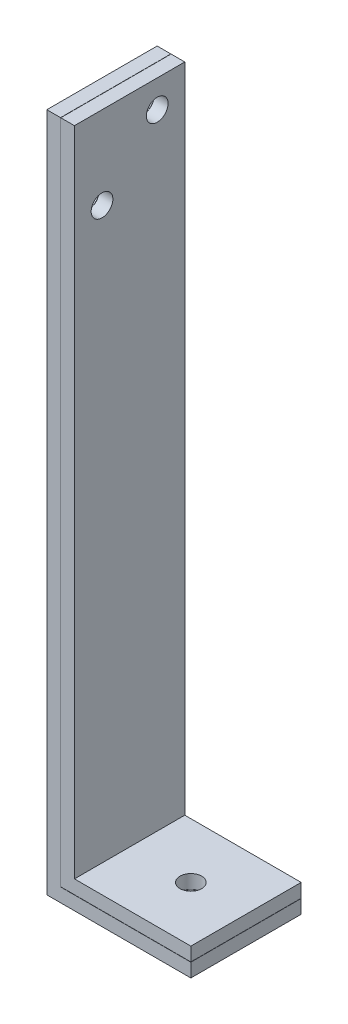
SolidWorks part; units mm, degrees
ref_plane "Alzado" through (0, 0, 0) normal (0, 0, 1) x (1, 0, 0)
ref_plane "Planta" through (0, 0, 0) normal (0, 1, 0) x (1, 0, 0)
ref_plane "Vista lateral" through (0, 0, 0) normal (1, 0, 0) x (0, 0, -1)
sketch "Croquis1" plane through (0, 0, 0) normal (0, 0, 1) x (1, 0, 0)
  line L0 (0, 0) -> (66.31, 0)
  line L1 (0, 0) -> (0, 313.04)
  line L2 (6.31, 6.31) -> (66.31, 6.31)
  line L3 (6.31, 6.31) -> (6.31, 313.04)
  line L4 (66.31, 6.31) -> (66.31, 0)
  line L5 (6.31, 313.04) -> (0, 313.04)
  dimension "D1" = 66.31
  dimension "D2" = 313.04
  dimension "D3" = 6.31
extrude "Saliente-Extruir1" add sketch "Croquis1" along normal blind 50.8
sketch "Croquis2" plane through (0, 0, 50.8) normal (0, 0, 1) x (1, 0, 0)
  line L0 (6.41, 313.04) -> (12.72, 313.04)
  line L1 (12.72, 313.04) -> (12.72, 12.72)
  line L2 (12.72, 12.72) -> (66.31, 12.72)
  line L3 (66.31, 12.72) -> (66.31, 6.41)
  line L4 (66.31, 6.41) -> (6.41, 6.41)
  line L5 (6.41, 6.41) -> (6.41, 313.04)
  line L6 (6.31, 6.31) -> (6.31, 313.04) construction
  line L7 (66.31, 6.31) -> (6.31, 6.31) construction
  line L9 (66.31, 6.31) -> (66.31, 6.9586) construction
  line L10 (6.31, 313.04) -> (0, 313.04) construction
  line L11 (3.155, 313.04) -> (16.3816, 313.04) construction
  dimension "D1" = 0.1
  dimension "D2" = 0.1
  dimension "D3" = 6.31
  dimension "D4" = 6.31
extrude "Saliente-Extruir2" add sketch "Croquis2" against normal blind 50.8 separate body
sketch "Croquis3" plane through (0, 0, 0) normal (-1, 0, 0) x (0, 0, 1)
  line L0 (0, 313.04) -> (50.8, 313.04) construction
  line L1 (50.8, 313.04) -> (50.8, 262.24) construction
  line L2 (50.8, 313.04) -> (50.8, 0) construction
  line L3 (50.8, 262.24) -> (0, 262.24) construction
  line L4 (0, 313.04) -> (0, 0) construction
  line L5 (0, 262.24) -> (0, 313.04) construction
  line L6 (0, 262.24) -> (50.8, 313.04) construction
  line L7 (50.8, 313.04) -> (25.4, 287.64) construction
  line L8 (25.4, 287.64) -> (38.1, 300.34) construction
  line L9 (50.8, 262.24) -> (0, 313.04) construction
  line L10 (25.4, 287.64) -> (0, 262.24) construction
  line L11 (0, 262.24) -> (12.7, 274.94) construction
  line L12 (0, 313.04) -> (25.4, 287.64) construction
  line L13 (25.4, 287.64) -> (12.7, 300.34) construction
  line L14 (12.7, 300.34) -> (19.05, 300.34) construction
  line L15 (25.4, 287.64) -> (50.8, 262.24) construction
  line L16 (50.8, 262.24) -> (38.1, 274.94) construction
  line L17 (38.1, 274.94) -> (27.9431, 274.94) construction
  line L18 (27.9431, 274.94) -> (27.9431, 273.0684) construction
  circle A0 centre (38.1, 274.94) radius 5
  circle A1 centre (12.7, 300.34) radius 5
  dimension "D2" = 10
  dimension "D3" = 10
  dimension "D1" = 50.8
sketch "Croquis5" plane through (0, 12.72, 0) normal (0, 1, 0) x (1, 0, 0)
  line L0 (36.243, -23.6058) -> (40.91, -25.4) construction
  line L1 (40.91, -25.4) -> (45.91, -25.4) construction
  circle A0 centre (40.91, -25.4) radius 5 construction
  circle A1 centre (40.91, -25.4) radius 5
extrude "Cortar-Extruir2" cut sketch "Croquis5" against normal blind 24.525
extrude "Cortar-Extruir3" cut sketch "Croquis3" against normal blind 29
